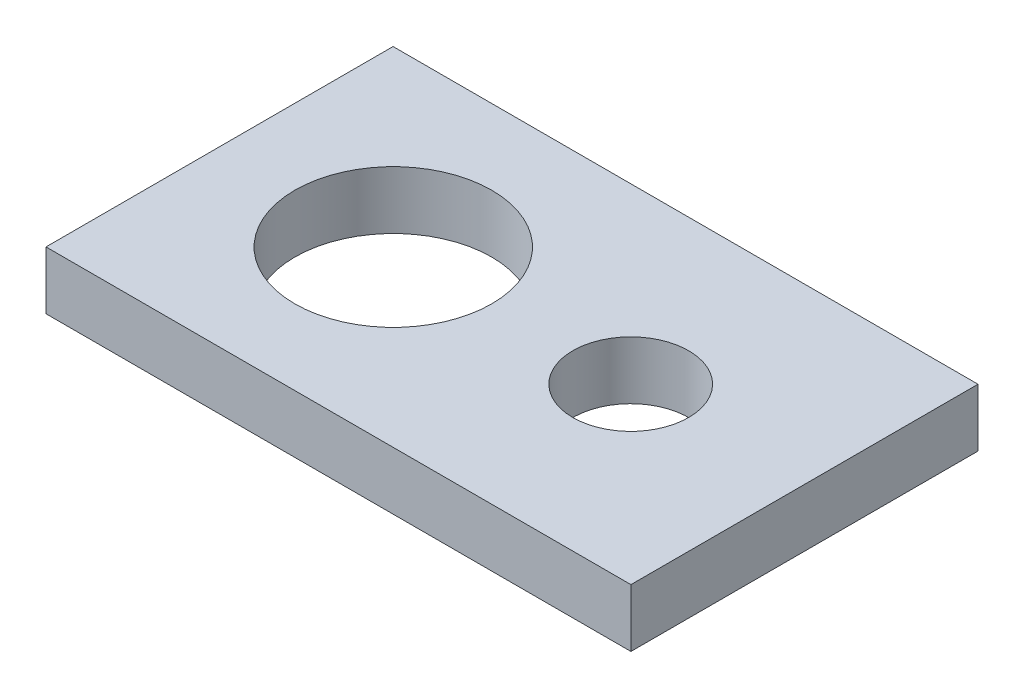
SolidWorks part; units mm, degrees
ref_plane "Front Plane" through (0, 0, 0) normal (0, 0, 1) x (1, 0, 0)
ref_plane "Top Plane" through (0, 0, 0) normal (0, 1, 0) x (1, 0, 0)
ref_plane "Right Plane" through (0, 0, 0) normal (1, 0, 0) x (0, 0, -1)
sketch "Sketch1" plane through (0, 0, 0) normal (0, 1, 0) x (1, 0, 0)
  line L0 (-50.5, 29.966) -> (9.5, 29.966) construction
  line L1 (-50.5, 29.966) -> (50.5, 29.966)
  line L2 (-50.5, 29.966) -> (-50.5, -29.966)
  line L3 (-50.5, -29.966) -> (50.5, -29.966)
  line L4 (50.5, 29.966) -> (50.5, -29.966)
  line L5 (-50.5, 29.966) -> (50.5, -29.966) construction
  line L6 (-50.5, -29.966) -> (50.5, 29.966) construction
  line L7 (9.5, 29.966) -> (9.5, -29.966) construction
  line L8 (-50.5, 29.966) -> (9.5, -29.966) construction
  line L9 (9.5, 29.966) -> (-50.5, -29.966) construction
  line L10 (-20.5, 0) -> (20.5, 0)
  circle A0 centre (-20.5, 0) radius 11
  circle A1 centre (20.5, 0) radius 10
  point P0 (0, 0)
  dimension "D1" = 22
  dimension "D3" = 20
  dimension "D4" = 30
  dimension "D5" = 41
  dimension "D2" = 60
extrude "Boss-Extrude1" add sketch "Sketch1" along normal blind 10
sketch "Sketch2" plane through (0, 10, 0) normal (0, 1, 0) x (1, 0, 0)
  circle A0 centre (-20.5, 0) radius 17
  dimension "D1" = 34
extrude "Cut-Extrude1" cut sketch "Sketch2" against normal blind 10
